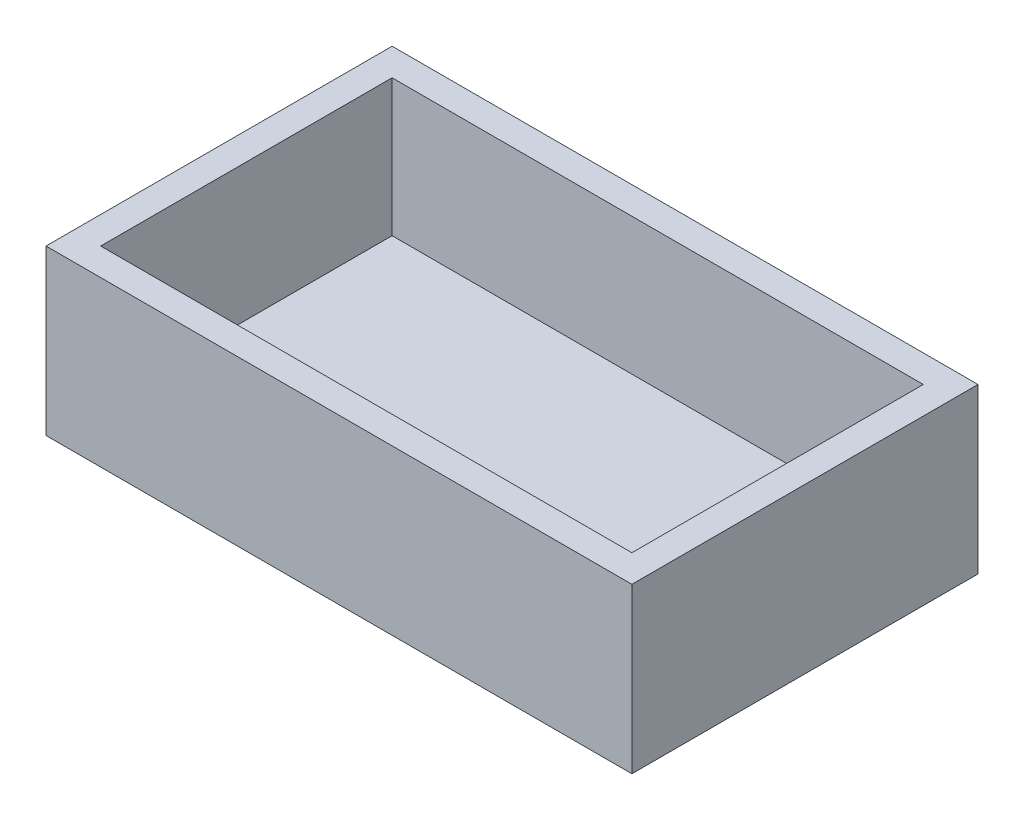
SolidWorks part; units mm, degrees
ref_plane "Plan de face" through (0, 0, 0) normal (0, 0, 1) x (1, 0, 0)
ref_plane "Plan de dessus" through (0, 0, 0) normal (0, 1, 0) x (1, 0, 0)
ref_plane "Plan de droite" through (0, 0, 0) normal (1, 0, 0) x (0, 0, -1)
sketch "Esquisse1" plane through (0, 0, 0) normal (0, 1, 0) x (1, 0, 0)
  line L1 (-107.1044, -63.2694) -> (107.1044, -63.2694)
  line L2 (-107.1044, -63.2694) -> (-107.1044, 63.2694)
  line L3 (-107.1044, 63.2694) -> (107.1044, 63.2694)
  line L4 (107.1044, -63.2694) -> (107.1044, 63.2694)
  line L5 (-107.1044, -63.2694) -> (107.1044, 63.2694) construction
  line L6 (-107.1044, 63.2694) -> (107.1044, -63.2694) construction
  point P0 (0, 0)
extrude "Boss.-Extru.1" add sketch "Esquisse1" along normal blind 60
shell "Coque2" thickness 10
